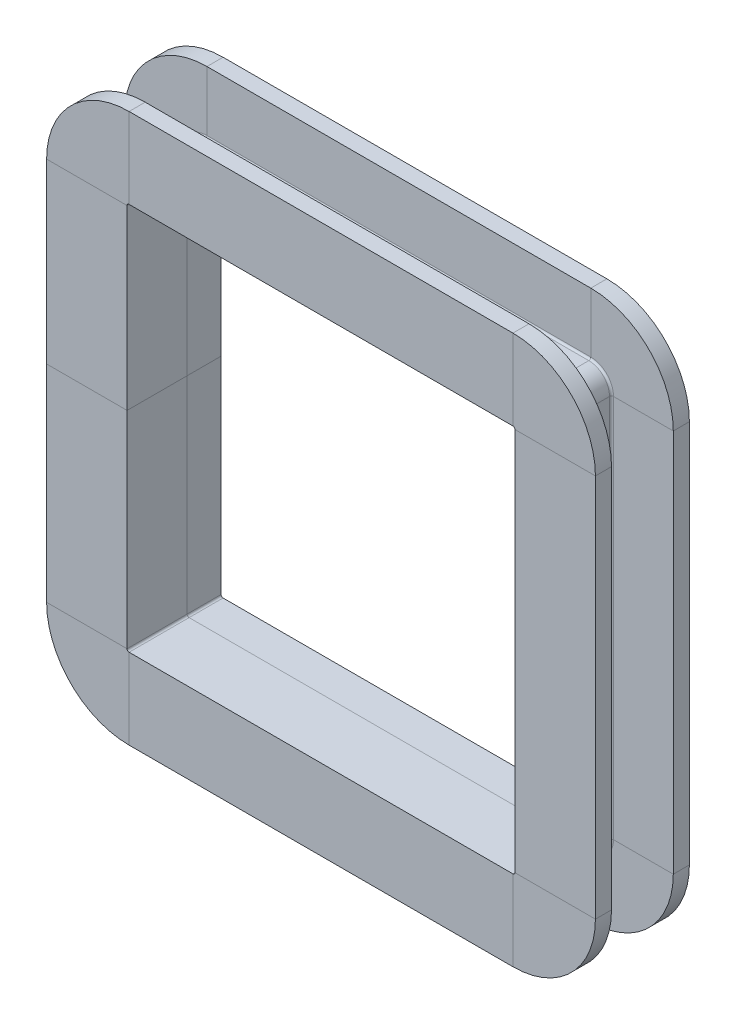
SolidWorks part; units mm, degrees
ref_plane "Front Plane" through (0, 0, 0) normal (0, 0, 1) x (1, 0, 0)
ref_plane "Top Plane" through (0, 0, 0) normal (0, 1, 0) x (1, 0, 0)
ref_plane "Right Plane" through (0, 0, 0) normal (1, 0, 0) x (0, 0, -1)
sketch "Sketch3" plane through (0, 0, 0) normal (0, 1, 0) x (1, 0, 0)
  line L0 (0, 0) -> (0, 10.725)
  line L1 (0, -55) -> (0, 55) construction
  line L2 (0, 0) -> (0, -18.935)
  line L3 (0, 10.725) -> (-25.4, 10.725)
  line L4 (-25.4, 10.725) -> (-25.4, 5.645)
  line L5 (-25.4, 5.645) -> (-6.535, 5.645)
  line L6 (-5.9, 5.01) -> (-5.9, -13.22)
  line L7 (0, -18.935) -> (-25.4, -18.935)
  line L8 (-25.4, -18.935) -> (-25.4, -13.855)
  line L9 (-25.4, -13.855) -> (-6.535, -13.855)
  arc A0 (-5.9, 5.01) -> (-6.535, 5.645) centre (-6.535, 5.01) ccw
  arc A1 (-5.9, -13.22) -> (-6.535, -13.855) centre (-6.535, -13.22) cw
  point P14 (-5.9, 5.645)
  point P17 (-5.9, -13.855)
  dimension "D7" = 0.635
  dimension "D1" = 5.08
  dimension "D2" = 5.08
  dimension "D3" = 25.4
  dimension "D5" = 19.5
  dimension "D6" = 19.5
sketch "Sketch4" plane through (0, 0, 0) normal (0, 0, 1) x (1, 0, 0)
  line L0 (0, -65.1549) -> (0, 56.0031)
  line L5 (0.635, 56.6381) -> (121.793, 56.6381)
  line L6 (122.428, 56.0031) -> (122.428, -65.1549)
  line L7 (121.793, -65.7899) -> (0.635, -65.7899)
  arc A0 (122.428, -65.1549) -> (121.793, -65.7899) centre (121.793, -65.1549) cw
  arc A1 (0, 56.0031) -> (0.635, 56.6381) centre (0.635, 56.0031) cw
  arc A2 (0.635, -65.7899) -> (0, -65.1549) centre (0.635, -65.1549) cw
  arc A3 (122.428, 56.0031) -> (121.793, 56.6381) centre (121.793, 56.0031) ccw
  point P8 (122.428, -65.7899)
  point P11 (0, 56.6381)
  point P16 (122.428, 56.6381)
  dimension "D3" = 0.635
  dimension "D4" = 0.635
  dimension "D1" = 122.428
  dimension "D2" = 122.428
sweep "Sweep1" add profiles "Sketch3" path "Sketch4"
